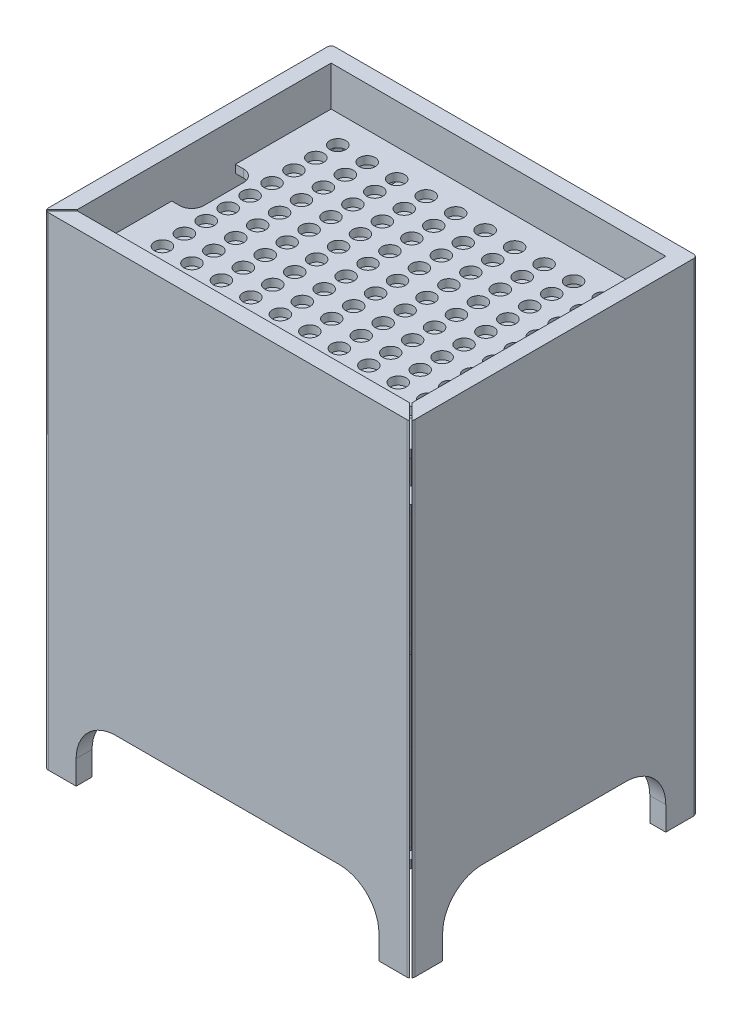
SolidWorks part; units mm, degrees
other "Filter size adapter"
other "screen+Prefilter"
other "Filter Hepa"
other "Filter VOC"
other "Base"
other "Mesh Screen"
ref_plane "Front Plane" through (0, 0, 0) normal (0, 0, 1) x (1, 0, 0)
ref_plane "Top Plane" through (0, 0, 0) normal (0, 1, 0) x (1, 0, 0)
ref_plane "Right Plane" through (0, 0, 0) normal (1, 0, 0) x (0, 0, -1)
sketch "Sketch1" plane through (0, 0, 0) normal (0, 1, 0) x (1, 0, 0)
  line L1 (-200, 150) -> (200, 150) construction
  line L2 (-200, 150) -> (-200, -150) construction
  line L3 (-200, -150) -> (200, -150) construction
  line L4 (200, 150) -> (200, -150) construction
  line L5 (-200, 150) -> (200, -150) construction
  line L6 (-200, -150) -> (200, 150) construction
  point P0 (0, 0)
  dimension "D1" = 300
  dimension "D2" = 400
ref_plane "Plane1" through (0, 100, 0) normal (0, 1, 0) x (1, 0, 0)
sketch "Sketch2" plane through (0, 100, 0) normal (0, 1, 0) x (1, 0, 0)
  line L1 (-200, -150) -> (200, -150) construction
  line L2 (-200, -150) -> (-200, 150) construction
  line L3 (-200, 150) -> (200, 150) construction
  line L4 (200, -150) -> (200, 150) construction
  line L5 (-200, -150) -> (200, 150) construction
  line L6 (-200, 150) -> (200, -150) construction
  line L7 (210, -160) -> (210, 160)
  line L8 (-210, 160) -> (210, 160)
  line L9 (-210, -160) -> (-210, 160)
  line L10 (-210, -160) -> (210, -160)
  line L11 (180, -105) -> (180, 105)
  line L12 (-155, 130) -> (155, 130)
  line L13 (-180, -105) -> (-180, 105)
  line L14 (-155, -130) -> (155, -130)
  line L15 (-180, -130) -> (-180, 130) construction
  line L16 (-180, -130) -> (180, -130) construction
  line L17 (180, -130) -> (180, 130) construction
  line L18 (-180, 130) -> (180, 130) construction
  arc A0 (-180, -105) -> (-155, -130) centre (-155, -105) ccw
  arc A1 (180, -105) -> (155, -130) centre (155, -105) cw
  arc A2 (180, 105) -> (155, 130) centre (155, 105) ccw
  arc A3 (-155, 130) -> (-180, 105) centre (-155, 105) ccw
  point P0 (0, 0)
  dimension "D5" = 25
  dimension "D1" = 300
  dimension "D2" = 400
  dimension "D3" = 10
  dimension "D4" = 20
extrude "Boss-Extrude1" add sketch "Sketch2" along normal blind 10
sketch "Sketch3" plane through (0, 0, 160) normal (0, 0, 1) x (1, 0, 0)
  line L1 (0, 110) -> (0, 0) construction
  line L2 (-210, 110) -> (210, 110) construction
  line L4 (-210, 0) -> (210, 0)
  line L5 (-210, 0) -> (-210, 560.413)
  line L6 (-210, 560.413) -> (210, 560.413)
  line L7 (210, 0) -> (210, 560.413)
sketch "Sketch6" plane through (0, 110, 0) normal (0, 1, 0) x (1, 0, 0)
  line L8 (-200, -150) -> (200, -150)
  line L9 (200, -150) -> (200, 150)
  line L10 (200, 150) -> (-200, 150)
  line L11 (-200, 150) -> (-200, -150)
  line L12 (-200, -150) -> (200, -150)
  line L13 (200, -150) -> (200, 150)
  line L14 (200, 150) -> (-200, 150)
  line L15 (-200, 150) -> (-200, -150)
  dimension "D1" = 10
extrude "Boss-Extrude4" add sketch "Sketch6" along normal blind 3 separate body
sketch "Sketch4" plane through (0, 113, 0) normal (0, 1, 0) x (1, 0, 0)
  line L1 (-200, 150) -> (200, -150) construction
  line L2 (-200, -150) -> (200, -150)
  line L3 (-200, -150) -> (-200, 150)
  line L4 (-200, 150) -> (200, 150)
  line L5 (200, -150) -> (200, 150)
  line L6 (-200, -150) -> (200, 150) construction
  line L7 (-200, 150) -> (200, -150) construction
  point P3 (0, 0)
extrude "Boss-Extrude2" add sketch "Sketch4" along normal blind 110 separate body
sketch "Sketch5" plane through (0, 223, 0) normal (0, 1, 0) x (1, 0, 0)
  line L4 (200, -150) -> (200, 150)
  line L5 (200, 150) -> (-200, 150)
  line L6 (-200, 150) -> (-200, -150)
  line L7 (-200, -150) -> (200, -150)
  line L8 (200, -150) -> (200, 150)
  line L9 (200, 150) -> (-200, 150)
  line L10 (-200, 150) -> (-200, -150)
  line L11 (-200, -150) -> (200, -150)
  dimension "D1" = 0
extrude "Boss-Extrude3" add sketch "Sketch5" along normal blind 110 separate body
sketch "Sketch7" plane through (0, 333, 0) normal (0, 1, 0) x (1, 0, 0)
  line L4 (-180, -130) -> (180, -130)
  line L5 (180, -130) -> (180, 130)
  line L6 (180, 130) -> (-180, 130)
  line L7 (-180, 130) -> (-180, -130)
  line L8 (-210, -160) -> (210, -160)
  line L9 (210, -160) -> (210, 160)
  line L10 (210, 160) -> (-210, 160)
  line L11 (-210, 160) -> (-210, -160)
  line L12 (-210, -160) -> (210, -160)
  line L13 (210, -160) -> (210, 160)
  line L14 (210, 160) -> (-210, 160)
  line L15 (-210, 160) -> (-210, -160)
  dimension "D1" = 10
  dimension "D2" = 30
extrude "Boss-Extrude5" add sketch "Sketch7" along normal blind 3 separate body
sketch "Sketch8" plane through (0, 336, 0) normal (0, 1, 0) x (1, 0, 0)
  line L0 (-190, 140) -> (-190, -140)
  line L1 (-190, -140) -> (190, -140)
  line L2 (190, -140) -> (190, 140)
  line L3 (190, 140) -> (-190, 140)
  line L4 (-210, 160) -> (-210, -160)
  line L5 (-210, -160) -> (210, -160)
  line L6 (210, -160) -> (210, 160)
  line L7 (210, 160) -> (-210, 160)
  line L8 (-210, 160) -> (-210, -160)
  line L9 (-210, -160) -> (210, -160)
  line L10 (210, -160) -> (210, 160)
  line L11 (210, 160) -> (-210, 160)
  dimension "D1" = 0
  dimension "D2" = 20
extrude "Boss-Extrude6" add sketch "Sketch8" along normal blind 20 separate body
sketch "Sketch9" plane through (0, 356, 0) normal (0, 1, 0) x (1, 0, 0)
  line L0 (195, 145) -> (-195, 145)
  line L1 (85, -110) -> (-85, -110) construction
  line L2 (110, -85) -> (110, 85) construction
  line L3 (85, 110) -> (-85, 110) construction
  line L12 (-110, -85) -> (-110, 85) construction
  line L13 (110, -110) -> (-110, 110) construction
  line L14 (110, 110) -> (-110, -110) construction
  line L15 (-195, 145) -> (-195, -145)
  line L16 (-195, -145) -> (195, -145)
  line L17 (195, -145) -> (195, 145)
  arc A0 (85, -110) -> (110, -85) centre (85, -85) ccw construction
  arc A1 (110, 85) -> (85, 110) centre (85, 85) ccw construction
  arc A2 (-85, 110) -> (-110, 85) centre (-85, 85) ccw construction
  arc A3 (-85, -110) -> (-110, -85) centre (-85, -85) cw construction
  circle A4 centre (0, 0) radius 110
  point P2 (0, 0)
  dimension "D4" = 25
  dimension "D2" = 220
  dimension "D3" = 220
extrude "Boss-Extrude7" add sketch "Sketch9" along normal blind 10 separate body
sketch "Sketch10" plane through (0, 356, 0) normal (0, 1, 0) x (1, 0, 0)
  line L4 (210, 160) -> (-210, 160)
  line L5 (-210, 160) -> (-210, -160)
  line L6 (-210, -160) -> (210, -160)
  line L7 (210, -160) -> (210, 160)
  line L8 (210, 160) -> (-210, 160)
  line L9 (-210, 160) -> (-210, -160)
  line L10 (-210, -160) -> (210, -160)
  line L11 (210, -160) -> (210, 160)
  line L12 (195, -145) -> (195, 145)
  line L13 (195, 145) -> (-195, 145)
  line L14 (-195, 145) -> (-195, -145)
  line L15 (-195, -145) -> (195, -145)
  line L16 (195, -145) -> (195, 145)
  line L17 (195, 145) -> (-195, 145)
  line L18 (-195, 145) -> (-195, -145)
  line L19 (-195, -145) -> (195, -145)
  dimension "D1" = 0
  dimension "D2" = 0
extrude "Boss-Extrude8" add sketch "Sketch10" along normal blind 130 separate body
sketch "Sketch11" plane through (0, 486, 0) normal (0, 1, 0) x (1, 0, 0)
  line L4 (210, -160) -> (210, 160)
  line L5 (210, 160) -> (-210, 160)
  line L6 (-210, 160) -> (-210, -160)
  line L7 (-210, -160) -> (210, -160)
  line L8 (210, -160) -> (210, 160)
  line L9 (210, 160) -> (-210, 160)
  line L10 (-210, 160) -> (-210, -160)
  line L11 (-210, -160) -> (210, -160)
  circle A0 centre (0, 0) radius 110 construction
  circle A1 centre (0, 0) radius 110
  dimension "D1" = 0
extrude "Boss-Extrude9" add sketch "Sketch11" along normal blind 10 separate body
sketch "Sketch12" plane through (0, 496, 0) normal (0, 1, 0) x (1, 0, 0)
  line L4 (0, -140) -> (0, 140) construction
  line L5 (0, 0) -> (190, 0) construction
  line L6 (190, -140) -> (175, -140)
  line L7 (190, -140) -> (190, -40)
  line L8 (-190, -140) -> (190, -140)
  line L9 (190, -140) -> (190, 140)
  line L10 (190, 140) -> (-190, 140)
  line L11 (-190, 140) -> (-190, -140)
  line L12 (-190, -140) -> (190, -140) construction
  line L13 (190, -140) -> (190, 140) construction
  line L14 (190, 140) -> (-190, 140) construction
  line L15 (-190, 140) -> (-190, -140) construction
  line L16 (190, -40) -> (175, -40)
  line L17 (175, -140) -> (175, -40)
  line L18 (190, 140) -> (175, 140)
  line L19 (190, 140) -> (190, 40)
  line L20 (190, 40) -> (175, 40)
  line L21 (175, 140) -> (175, 40)
  line L22 (-100, -140) -> (100, -140)
  line L23 (0, -140) -> (0, -125)
  line L24 (-100, -125) -> (100, -125)
  line L25 (100, -140) -> (100, -125)
  line L26 (0, 140) -> (0, 125)
  line L27 (-100, 140) -> (100, 140)
  line L28 (100, 140) -> (100, 125)
  line L29 (-100, 125) -> (100, 125)
  line L30 (-190, 140) -> (-175, 140)
  line L31 (-190, 140) -> (-190, 40)
  line L32 (-190, 40) -> (-175, 40)
  line L33 (-175, 140) -> (-175, 40)
  line L34 (-100, 140) -> (-100, 125)
  line L35 (-100, -140) -> (-100, -125)
  line L36 (-190, -140) -> (-175, -140)
  line L37 (-190, -140) -> (-190, -40)
  line L38 (-190, -40) -> (-175, -40)
  line L39 (-175, -140) -> (-175, -40)
  dimension "D2" = 100
  dimension "D3" = 100
  dimension "D4" = 15
  dimension "D5" = 100
  dimension "D6" = 15
  dimension "D1" = 20
extrude "Boss-Extrude10" add sketch "Sketch12" along normal blind 50 separate body contours L27 L34 L29 L26 | L26 L29 L28 L27 | L18 L21 L20 L19 | L17 L6 L7 L16 | L22 L25 L24 L23 | L35 L22 L23 L24 | L36 L39 L38 L37 | L33 L30 L31 L32
sketch "Sketch13" plane through (0, 546, 0) normal (0, 1, 0) x (1, 0, 0)
  line L4 (-210, -160) -> (210, -160)
  line L5 (210, -160) -> (210, 160)
  line L6 (210, 160) -> (-210, 160)
  line L7 (-210, 160) -> (-210, -160)
  line L8 (-210, -160) -> (210, -160)
  line L9 (210, -160) -> (210, 160)
  line L10 (210, 160) -> (-210, 160)
  line L11 (-210, 160) -> (-210, -160)
  dimension "D1" = 0
extrude "Boss-Extrude11" add sketch "Sketch13" along normal blind 10 separate body
sketch "Sketch14" plane through (0, 556, 0) normal (0, 1, 0) x (1, 0, 0)
  line L0 (-200, 150) -> (200, -150) construction
  line L1 (166.6667, -125) -> (-166.6667, -125) construction
  line L2 (166.6667, -125) -> (166.6667, 125) construction
  line L3 (166.6667, 125) -> (-166.6667, 125) construction
  line L4 (-166.6667, -125) -> (-166.6667, 125) construction
  line L5 (166.6667, -125) -> (-166.6667, 125) construction
  line L6 (166.6667, 125) -> (-166.6667, -125) construction
  line L7 (-100, -140) -> (100, -140) construction
  line L8 (190, -140) -> (190, -40) construction
  line L9 (-190, -140) -> (-190, -40) construction
  line L10 (-190, 140) -> (-190, 40) construction
  line L11 (-100, 140) -> (100, 140) construction
  line L12 (190, 140) -> (190, 40) construction
  line L13 (-100, -140) -> (100, -140) construction
  line L14 (190, -140) -> (190, -40) construction
  line L15 (-190, -140) -> (-190, -40) construction
  line L16 (-190, 140) -> (-190, 40) construction
  line L17 (-100, 140) -> (100, 140) construction
  line L18 (190, 140) -> (190, 40) construction
  circle A0 centre (-166.6667, 125) radius 10
  circle A1 centre (-129.6667, 125) radius 10
  circle A2 centre (-92.6667, 125) radius 10
  circle A3 centre (-55.6667, 125) radius 10
  circle A4 centre (-18.6667, 125) radius 10
  circle A5 centre (18.3333, 125) radius 10
  circle A6 centre (55.3333, 125) radius 10
  circle A7 centre (92.3333, 125) radius 10
  circle A8 centre (129.3333, 125) radius 10
  circle A9 centre (166.3333, 125) radius 10
  circle A10 centre (-166.6667, 97.5) radius 10
  circle A11 centre (-129.6667, 97.5) radius 10
  circle A12 centre (-92.6667, 97.5) radius 10
  circle A13 centre (-55.6667, 97.5) radius 10
  circle A14 centre (-18.6667, 97.5) radius 10
  circle A15 centre (18.3333, 97.5) radius 10
  circle A16 centre (55.3333, 97.5) radius 10
  circle A17 centre (92.3333, 97.5) radius 10
  circle A18 centre (129.3333, 97.5) radius 10
  circle A19 centre (166.3333, 97.5) radius 10
  circle A20 centre (-166.6667, 70) radius 10
  circle A21 centre (-129.6667, 70) radius 10
  circle A22 centre (-92.6667, 70) radius 10
  circle A23 centre (-55.6667, 70) radius 10
  circle A24 centre (-18.6667, 70) radius 10
  circle A25 centre (18.3333, 70) radius 10
  circle A26 centre (55.3333, 70) radius 10
  circle A27 centre (92.3333, 70) radius 10
  circle A28 centre (129.3333, 70) radius 10
  circle A29 centre (166.3333, 70) radius 10
  circle A30 centre (-166.6667, 42.5) radius 10
  circle A31 centre (-129.6667, 42.5) radius 10
  circle A32 centre (-92.6667, 42.5) radius 10
  circle A33 centre (-55.6667, 42.5) radius 10
  circle A34 centre (-18.6667, 42.5) radius 10
  circle A35 centre (18.3333, 42.5) radius 10
  circle A36 centre (55.3333, 42.5) radius 10
  circle A37 centre (92.3333, 42.5) radius 10
  circle A38 centre (129.3333, 42.5) radius 10
  circle A39 centre (166.3333, 42.5) radius 10
  circle A40 centre (-166.6667, 15) radius 10
  circle A41 centre (-129.6667, 15) radius 10
  circle A42 centre (-92.6667, 15) radius 10
  circle A43 centre (-55.6667, 15) radius 10
  circle A44 centre (-18.6667, 15) radius 10
  circle A45 centre (18.3333, 15) radius 10
  circle A46 centre (55.3333, 15) radius 10
  circle A47 centre (92.3333, 15) radius 10
  circle A48 centre (129.3333, 15) radius 10
  circle A49 centre (166.3333, 15) radius 10
  circle A50 centre (-166.6667, -12.5) radius 10
  circle A51 centre (-129.6667, -12.5) radius 10
  circle A52 centre (-92.6667, -12.5) radius 10
  circle A53 centre (-55.6667, -12.5) radius 10
  circle A54 centre (-18.6667, -12.5) radius 10
  circle A55 centre (18.3333, -12.5) radius 10
  circle A56 centre (55.3333, -12.5) radius 10
  circle A57 centre (92.3333, -12.5) radius 10
  circle A58 centre (129.3333, -12.5) radius 10
  circle A59 centre (166.3333, -12.5) radius 10
  circle A60 centre (-166.6667, -40) radius 10
  circle A61 centre (-129.6667, -40) radius 10
  circle A62 centre (-92.6667, -40) radius 10
  circle A63 centre (-55.6667, -40) radius 10
  circle A64 centre (-18.6667, -40) radius 10
  circle A65 centre (18.3333, -40) radius 10
  circle A66 centre (55.3333, -40) radius 10
  circle A67 centre (92.3333, -40) radius 10
  circle A68 centre (129.3333, -40) radius 10
  circle A69 centre (166.3333, -40) radius 10
  circle A70 centre (-166.6667, -67.5) radius 10
  circle A71 centre (-129.6667, -67.5) radius 10
  circle A72 centre (-92.6667, -67.5) radius 10
  circle A73 centre (-55.6667, -67.5) radius 10
  circle A74 centre (-18.6667, -67.5) radius 10
  circle A75 centre (18.3333, -67.5) radius 10
  circle A76 centre (55.3333, -67.5) radius 10
  circle A77 centre (92.3333, -67.5) radius 10
  circle A78 centre (129.3333, -67.5) radius 10
  circle A79 centre (166.3333, -67.5) radius 10
  circle A80 centre (-166.6667, -95) radius 10
  circle A81 centre (-129.6667, -95) radius 10
  circle A82 centre (-92.6667, -95) radius 10
  circle A83 centre (-55.6667, -95) radius 10
  circle A84 centre (-18.6667, -95) radius 10
  circle A85 centre (18.3333, -95) radius 10
  circle A86 centre (55.3333, -95) radius 10
  circle A87 centre (92.3333, -95) radius 10
  circle A88 centre (129.3333, -95) radius 10
  circle A89 centre (166.3333, -95) radius 10
  circle A90 centre (-166.6667, -122.5) radius 10
  circle A91 centre (-129.6667, -122.5) radius 10
  circle A92 centre (-92.6667, -122.5) radius 10
  circle A93 centre (-55.6667, -122.5) radius 10
  circle A94 centre (-18.6667, -122.5) radius 10
  circle A95 centre (18.3333, -122.5) radius 10
  circle A96 centre (55.3333, -122.5) radius 10
  circle A97 centre (92.3333, -122.5) radius 10
  circle A98 centre (129.3333, -122.5) radius 10
  circle A99 centre (166.3333, -122.5) radius 10
  point P0 (0, 0)
  dimension "D2" = 10
  dimension "D1" = 250
  dimension "D3" = 10
extrude "Cut-Extrude1" cut sketch "Sketch14" against normal up to next (10 mm away)
sketch "Sketch15" plane through (0, 556, 0) normal (0, 1, 0) x (1, 0, 0)
  line L0 (210, 0) -> (-210, 0) construction
  line L1 (210, -160) -> (210, 160) construction
  line L2 (-210, 160) -> (-210, -160) construction
  line L3 (190, 40) -> (175, 40) construction
  line L4 (190, -40) -> (175, -40) construction
  line L5 (210, 40) -> (200, 40)
  line L6 (210, -40) -> (200, -40)
  line L7 (185, 25) -> (185, -25)
  line L8 (210, 40) -> (210, -40)
  line L9 (0, -160) -> (0, 160) construction
  line L10 (-210, -160) -> (210, -160) construction
  line L11 (210, 160) -> (-210, 160) construction
  line L12 (-185, 25) -> (-185, -25)
  line L13 (-210, -40) -> (-200, -40)
  line L14 (-210, 40) -> (-210, -40)
  line L15 (-210, 40) -> (-200, 40)
  arc A0 (185, -25) -> (200, -40) centre (200, -25) ccw
  arc A1 (185, 25) -> (200, 40) centre (200, 25) cw
  arc A2 (-185, -25) -> (-200, -40) centre (-200, -25) cw
  arc A3 (-185, 25) -> (-200, 40) centre (-200, 25) ccw
  dimension "D1" = 15
  dimension "D2" = 25
extrude "Cut-Extrude2" cut sketch "Sketch15" against normal up to next (10 mm away)
sketch "Sketch16" plane through (0, 546, 0) normal (0, -1, 0) x (1, 0, 0)
  line L1 (176.3333, -125) -> (176.3333, 125)
  line L2 (-100, 125) -> (100, 125) construction
  line L3 (-100, -125) -> (100, -125) construction
  line L4 (-176.3491, 125) -> (100, 125)
  line L5 (-176.6667, -125) -> (176.3333, -125)
  line L6 (100, 125) -> (176.3333, 125)
  line L8 (-176.6667, -125) -> (-176.3491, 125)
  circle A0 centre (166.3333, -125) radius 10 construction
  circle A2 centre (-166.6667, -125) radius 10 construction
  circle A3 centre (-166.6667, 122.5) radius 10 construction
extrude "Boss-Extrude12" add sketch "Sketch16" along normal blind 2 separate body
sketch "Sketch17" plane through (0, 0, -160) normal (0, 0, -1) x (-1, 0, 0)
  line L0 (-210, 556) -> (210, 556) construction
  line L1 (-210, 556) -> (210, 556)
  line L2 (-210, 556) -> (-210, 0)
  line L3 (210, 556) -> (210, 0)
sketch "Sketch18" plane through (0, 556, 0) normal (0, 1, 0) x (1, 0, 0)
  line L0 (-230, -180) -> (230, -180)
  line L1 (230, -180) -> (230, 180)
  line L2 (230, 180) -> (-230, 180)
  line L3 (-230, 180) -> (-230, -180)
  line L4 (-210, -160) -> (210, -160)
  line L5 (210, -160) -> (210, 160)
  line L6 (210, 160) -> (-210, 160)
  line L7 (-210, 160) -> (-210, -160)
  line L8 (-210, -160) -> (210, -160)
  line L9 (210, -160) -> (210, 160)
  line L10 (210, 160) -> (-210, 160)
  line L11 (-210, 160) -> (-210, -160)
  dimension "D1" = 0
  dimension "D2" = 20
extrude "Boss-Extrude14" add sketch "Sketch18" along normal blind 50 and the other way up to vertex (556 mm away) separate body other way up to point (210, 0, -160)
sketch "Sketch19" plane through (0, 0, 160) normal (0, 0, -1) x (-1, 0, 0)
  line L0 (210, 100) -> (-210, 100) construction
  line L1 (210, 100) -> (-210, 100) construction
  line L2 (-210, 100) -> (-210, 0) construction
  line L3 (210, 100) -> (210, 0) construction
  line L4 (-190, 30) -> (-190, 0)
  line L5 (140, 80) -> (-140, 80)
  line L6 (190, 30) -> (190, 0)
  line L7 (-190, 0) -> (190, 0)
  line L8 (190, 80) -> (-190, 80) construction
  line L9 (190, 80) -> (190, 0) construction
  line L10 (-190, 80) -> (-190, 0) construction
  arc A0 (140, 80) -> (190, 30) centre (140, 30) cw
  arc A1 (-190, 30) -> (-140, 80) centre (-140, 30) cw
  dimension "D2" = 50
  dimension "D1" = 20
extrude "Cut-Extrude3" cut sketch "Sketch19" along normal through all and the other way blind 50
sketch "Sketch20" plane through (-210, 0, 0) normal (1, 0, 0) x (0, 0, -1)
  line L0 (160, 100) -> (-160, 100) construction
  line L1 (160, 100) -> (-160, 100) construction
  line L2 (160, 100) -> (160, 0) construction
  line L3 (-140, 0) -> (-140, 30)
  line L4 (-160, 0) -> (-160, 100) construction
  line L5 (90, 80) -> (-90, 80)
  line L6 (140, 30) -> (140, 0)
  line L7 (140, 80) -> (-140, 80) construction
  line L8 (140, 80) -> (140, 0) construction
  line L9 (-140, 0) -> (-140, 80) construction
  line L10 (-140, 0) -> (140, 0)
  arc A0 (90, 80) -> (140, 30) centre (90, 30) cw
  arc A1 (-140, 30) -> (-90, 80) centre (-90, 30) cw
  dimension "D2" = 50
  dimension "D1" = 20
extrude "Cut-Extrude4" cut sketch "Sketch20" against normal blind 50 and the other way through all
fillet "Fillet1" radius 5 4 edges at (-230, 303, -180) (-230, 303, 180) (230, 303, -180) (230, 303, 180)
sketch "Sketch21" plane through (0, 606, 0) normal (0, 1, 0) x (1, 0, 0)
  line L0 (-210, -160) -> (-228.5355, -178.5355) construction
  line L1 (210, -160) -> (228.5355, -178.5355) construction
  line L2 (207.8433, -159.2575) -> (227.8284, -179.2426)
  line L3 (209.3318, -157.9176) -> (229.2426, -177.8284)
  line L4 (229.2426, -177.8284) -> (227.8284, -179.2426)
  line L5 (210.7071, -159.2929) -> (229.2426, -177.8284) construction
  line L6 (209.2929, -160.7071) -> (227.8284, -179.2426) construction
  line L7 (209.3318, -157.9176) -> (207.8433, -159.2575)
  line L8 (-209.9239, -158.5097) -> (-229.2426, -177.8284)
  line L9 (-208.2354, -159.6496) -> (-227.8284, -179.2426)
  line L10 (-209.2929, -160.7071) -> (-227.8284, -179.2426) construction
  line L11 (-210.7071, -159.2929) -> (-229.2426, -177.8284) construction
  line L12 (-208.2354, -159.6496) -> (-209.9239, -158.5097)
  line L13 (-227.8284, -179.2426) -> (-229.2426, -177.8284)
  arc A0 (-230, -175) -> (-225, -180) centre (-225, -175) ccw construction
  arc A1 (225, -180) -> (230, -175) centre (225, -175) ccw construction
  dimension "D1" = 1
  dimension "D2" = 1
  dimension "D3" = 1
  dimension "D4" = 1
extrude "Cut-Extrude5" cut sketch "Sketch21" against normal up to vertex
